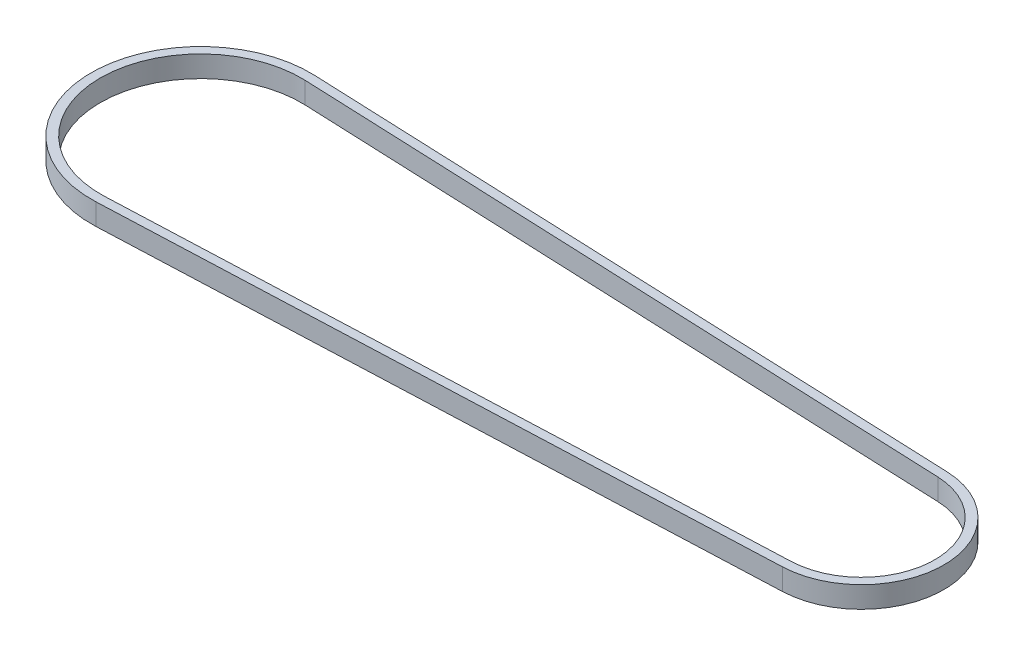
SolidWorks part; units mm, degrees
ref_plane "Front Plane" through (0, 0, 0) normal (0, 0, 1) x (1, 0, 0)
ref_plane "Top Plane" through (0, 0, 0) normal (0, 1, 0) x (1, 0, 0)
ref_plane "Right Plane" through (0, 0, 0) normal (1, 0, 0) x (0, 0, -1)
sketch "Sketch1" plane through (0, 0, 0) normal (0, 1, 0) x (1, 0, 0)
  line L0 (0, 0) -> (185.42, 0) construction
  line L1 (186.2655, -20.5566) -> (1.1587, -28.1702)
  line L2 (186.2655, 20.5566) -> (1.1587, 28.1702)
  line L3 (186.3699, -23.0945) -> (1.263, -30.708)
  line L4 (186.3699, 23.0945) -> (1.263, 30.708)
  arc A0 (1.1587, 28.1702) -> (1.1587, -28.1702) centre (0, 0) ccw
  arc A1 (186.2655, -20.5566) -> (186.2655, 20.5566) centre (185.42, 0) ccw
  arc A2 (1.263, 30.708) -> (1.263, -30.708) centre (0, 0) ccw
  arc A3 (186.3699, -23.0945) -> (186.3699, 23.0945) centre (185.42, 0) ccw
  dimension "D2" = 56.388
  dimension "D3" = 41.148
  dimension "D1" = 185.42
  dimension "D4" = 2.54
extrude "Boss-Extrude1" add sketch "Sketch1" along normal blind 6
